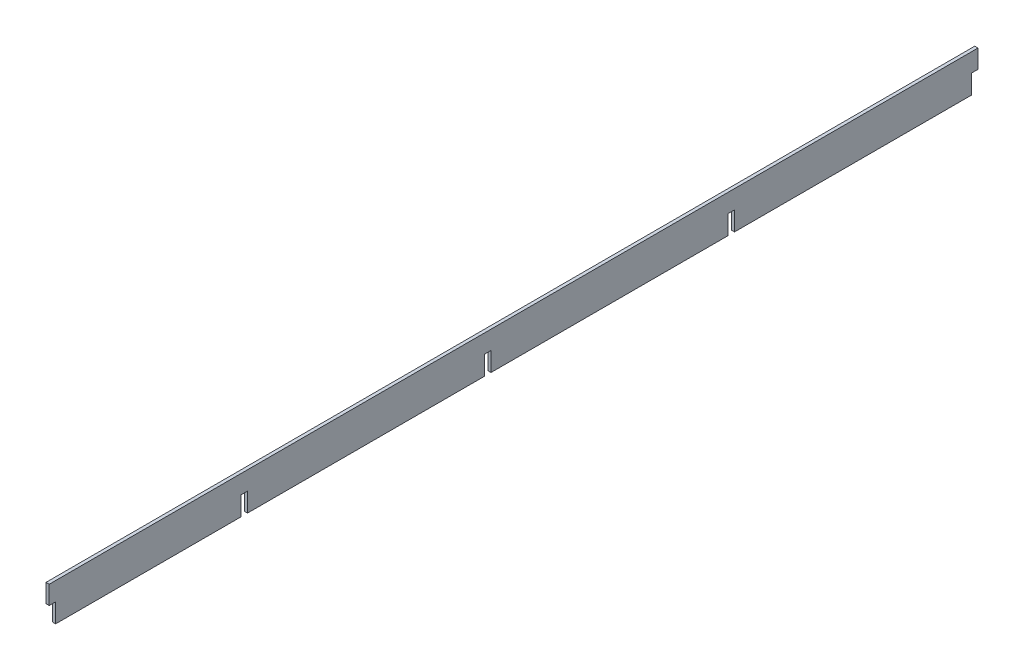
SolidWorks part; units mm, degrees
material "Balsa"
ref_plane "Front Plane" through (0, 0, 0) normal (0, 0, 1) x (1, 0, 0)
ref_plane "Top Plane" through (0, 0, 0) normal (0, 1, 0) x (1, 0, 0)
ref_plane "Right Plane" through (0, 0, 0) normal (1, 0, 0) x (0, 0, -1)
sketch "Sketch1" plane through (329.3139, 0, 0) normal (1, 0, 0) x (0, 0, -1)
  line L2 (-442.7124, 416.6706) -> (-439.5374, 416.6706) construction
  line L4 (-319.6812, 425.7668) -> (-322.8562, 425.7668)
  line L5 (-322.8562, 425.7668) -> (-322.8562, 416.6706)
  line L6 (-322.8562, 416.6706) -> (-319.6812, 416.6706)
  line L7 (-319.6812, 416.6706) -> (-319.6812, 425.7668)
  line L8 (-319.6812, 425.7668) -> (-322.8562, 425.7668)
  line L10 (-322.8562, 416.6706) -> (-319.6812, 416.6706)
  line L11 (-319.6812, 416.6706) -> (-319.6812, 425.7668)
  line L14 (-562.5687, 416.6706) -> (-559.3937, 416.6706) construction
  line L18 (-682.4249, 416.6706) -> (-679.2499, 416.6706) construction
  line L20 (-776.8812, 416.6706) -> (-773.7062, 416.6706) construction
  line L22 (-773.7062, 425.7668) -> (-776.8812, 425.7668) construction
  line L23 (-776.8812, 425.7668) -> (-776.8812, 416.6706) construction
  line L26 (-442.7124, 416.6706) -> (-439.5374, 416.6706)
  line L30 (-562.5687, 416.6706) -> (-559.3937, 416.6706)
  line L34 (-682.4249, 416.6706) -> (-679.2499, 416.6706)
  line L36 (-776.8812, 416.6706) -> (-773.7062, 416.6706)
  line L38 (-773.7062, 425.7668) -> (-776.8812, 425.7668)
  line L39 (-776.8812, 425.7668) -> (-776.8812, 416.6706)
  line L40 (-322.8562, 425.7668) -> (-773.7062, 425.7668)
  line L41 (-773.7062, 416.6706) -> (-773.7062, 407.28)
  line L42 (-773.7062, 407.28) -> (-682.4249, 407.28)
  line L43 (-322.8562, 407.28) -> (-322.8562, 416.6706)
  line L44 (-442.7124, 416.6706) -> (-442.7124, 407.28)
  line L45 (-439.5374, 416.6706) -> (-439.5374, 407.28)
  line L46 (-562.5687, 416.6706) -> (-562.5687, 407.28)
  line L47 (-559.3937, 416.6706) -> (-559.3937, 407.28)
  line L48 (-682.4249, 416.6706) -> (-682.4249, 407.28)
  line L49 (-679.2499, 416.6706) -> (-679.2499, 407.28)
  line L50 (-679.2499, 407.28) -> (-562.5687, 407.28)
  line L51 (-559.3937, 407.28) -> (-442.7124, 407.28)
  line L52 (-439.5374, 407.28) -> (-322.8562, 407.28)
  dimension "D1" = 0
extrude "Boss-Extrude1" add sketch "Sketch1" along normal up to surface (1.5875 mm away)
